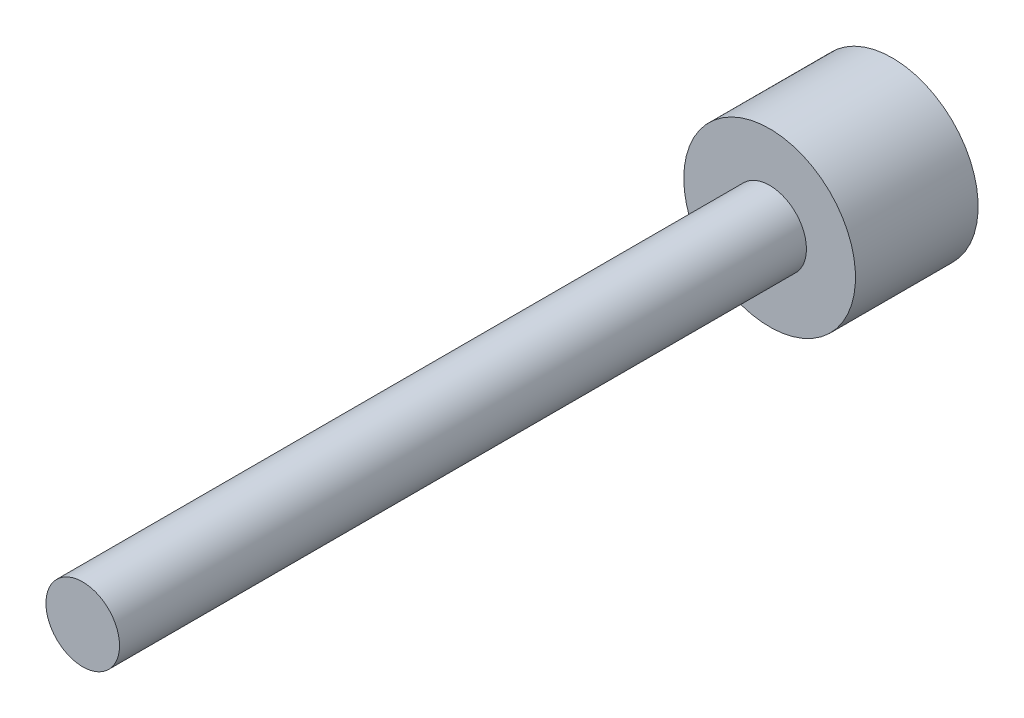
SolidWorks part; units mm, degrees
ref_plane "Plan de face" through (0, 0, 0) normal (0, 0, 1) x (1, 0, 0)
ref_plane "Plan de dessus" through (0, 0, 0) normal (0, 1, 0) x (1, 0, 0)
ref_plane "Plan de droite" through (0, 0, 0) normal (1, 0, 0) x (0, 0, -1)
sketch "Esquisse1" plane through (0, 0, 0) normal (0, 0, 1) x (1, 0, 0)
  circle A0 centre (0, 0) radius 1.5
  dimension "D1" = 3
extrude "Boss.-Extru.1" add sketch "Esquisse1" along normal blind 28
sketch "Esquisse2" plane through (0, 0, 0) normal (0, 0, -1) x (-1, 0, 0)
  circle A0 centre (0, 0) radius 3.5
  dimension "D1" = 7
extrude "Boss.-Extru.2" add sketch "Esquisse2" along normal blind 5
